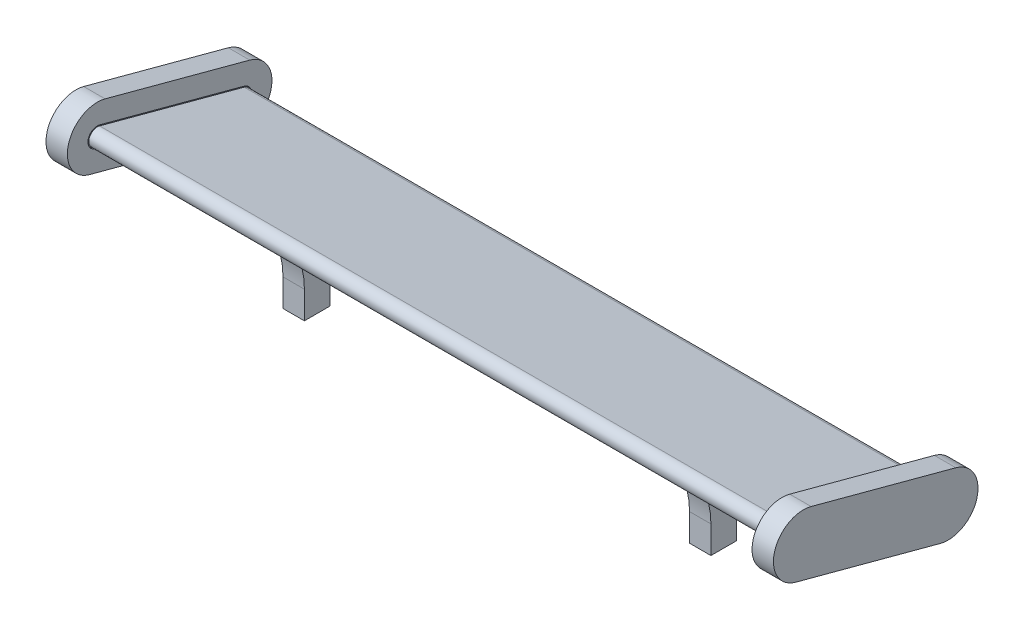
SolidWorks part; units mm, degrees
ref_plane "Front Plane" through (0, 0, 0) normal (0, 0, 1) x (1, 0, 0)
ref_plane "Top Plane" through (0, 0, 0) normal (0, 1, 0) x (1, 0, 0)
ref_plane "Right Plane" through (0, 0, 0) normal (1, 0, 0) x (0, 0, -1)
sketch "Sketch1" plane through (0, 0, 0) normal (1, 0, 0) x (0, 0, -1)
  line L0 (-16.9037, 4.5293) -> (16.9037, -4.5293) construction
  line L1 (-16.3867, 6.4589) -> (17.4207, -2.5997)
  line L2 (-17.4207, 2.5997) -> (16.3867, -6.4589)
  line L3 (0, 0) -> (31.3871, 0) construction
  arc A0 (-16.3867, 6.4589) -> (-17.4207, 2.5997) centre (-16.9037, 4.5293) ccw
  arc A1 (16.3867, -6.4589) -> (17.4207, -2.5997) centre (16.9037, -4.5293) ccw
  point P2 (0, 0)
  dimension "D1" = 15
  dimension "D2" = 35
  dimension "D3" = 3.9954
extrude "Boss-Extrude1" add sketch "Sketch1" along normal blind 80
sketch "Sketch2" plane through (80, 0, 0) normal (1, 0, 0) x (0, 0, -1)
  line L4 (-18.7148, -2.2299) -> (15.0926, -11.2886)
  line L5 (18.7148, 2.2299) -> (-15.0926, 11.2886)
  line L6 (-18.7148, -2.2299) -> (15.0926, -11.2886)
  line L7 (18.7148, 2.2299) -> (-15.0926, 11.2886)
  arc A4 (-15.0926, 11.2886) -> (-18.7148, -2.2299) centre (-16.9037, 4.5293) ccw
  arc A5 (15.0926, -11.2886) -> (18.7148, 2.2299) centre (16.9037, -4.5293) ccw
  arc A6 (-15.0926, 11.2886) -> (-18.7148, -2.2299) centre (-16.9037, 4.5293) ccw
  arc A7 (15.0926, -11.2886) -> (18.7148, 2.2299) centre (16.9037, -4.5293) ccw
  dimension "D1" = 5
extrude "Boss-Extrude2" add sketch "Sketch2" along normal blind 5 separate body
sketch "Sketch8" plane through (80, 0, 0) normal (-1, 0, 0) x (0, 0, 1)
  line L0 (17.4207, 2.5997) -> (-16.3867, -6.4589) construction
  line L1 (-17.4207, -2.5997) -> (16.3867, 6.4589) construction
  line L2 (17.4207, 2.5997) -> (-16.3867, -6.4589) construction
  line L3 (-17.4207, -2.5997) -> (16.3867, 6.4589) construction
  line L4 (-17.4725, -2.4065) -> (16.3349, 6.6521)
  line L5 (17.4725, 2.4065) -> (-16.3349, -6.6521)
  arc A0 (17.4207, 2.5997) -> (16.3867, 6.4589) centre (16.9037, 4.5293) ccw construction
  arc A1 (-17.4207, -2.5997) -> (-16.3867, -6.4589) centre (-16.9037, -4.5293) ccw construction
  arc A2 (17.4207, 2.5997) -> (16.3867, 6.4589) centre (16.9037, 4.5293) ccw construction
  arc A3 (-17.4207, -2.5997) -> (-16.3867, -6.4589) centre (-16.9037, -4.5293) ccw construction
  arc A4 (17.4725, 2.4065) -> (16.3349, 6.6521) centre (16.9037, 4.5293) ccw
  arc A5 (-17.4725, -2.4065) -> (-16.3349, -6.6521) centre (-16.9037, -4.5293) ccw
  dimension "D1" = 0.2
extrude "Cut-Extrude1" cut sketch "Sketch8" against normal blind 0.6 contours L4 A4 L5 A5
sketch "Sketch7" plane through (0, 0, 0) normal (-1, 0, 0) x (0, 0, 1)
  line L0 (0.517, -1.9296) -> (0.517, -21.9296) construction
  line L2 (-2.483, -17.1276) -> (-2.483, -21.9296)
  line L3 (3.517, -15.5199) -> (3.517, -21.9296)
  line L4 (3.517, -1.9296) -> (3.517, -21.9296) construction
  line L6 (-2.483, -1.9296) -> (-2.483, -21.9296) construction
  line L7 (-2.483, -21.9296) -> (3.517, -21.9296)
  line L8 (-6.7893, -5.9579) -> (6.1055, -2.5028) construction
  line L9 (16.3867, 6.4589) -> (-17.4207, -2.5997)
  line L10 (-16.3867, -6.4589) -> (17.4207, 2.5997)
  line L12 (-16.3867, -6.4589) -> (17.4207, 2.5997)
  line L13 (1.517, -15.5199) -> (1.517, -19.9296) construction
  line L14 (-0.483, -19.9296) -> (1.517, -19.9296) construction
  line L15 (-0.483, -17.1276) -> (-0.483, -19.9296) construction
  arc A0 (-16.3867, -6.4589) -> (-2.483, -17.1276) centre (-13.528, -17.1276) cw
  arc A1 (17.4207, 2.5997) -> (3.517, -15.5199) centre (22.2759, -15.5199) ccw
  arc A2 (17.4207, 2.5997) -> (16.3867, 6.4589) centre (16.9037, 4.5293) ccw
  arc A3 (-17.4207, -2.5997) -> (-16.3867, -6.4589) centre (-16.9037, -4.5293) ccw
  arc A6 (6.1055, -2.5028) -> (1.517, -15.5199) centre (22.2759, -15.5199) ccw construction
  arc A7 (-6.7893, -5.9579) -> (-0.483, -17.1276) centre (-13.528, -17.1276) cw construction
  point P2 (0, 0)
  point P3 (0, 0)
  dimension "D5" = 2
  dimension "D1" = 20
  dimension "D2" = 3
  dimension "D6" = 0.517
  dimension "D3" = 3
  dimension "D4" = 0
extrude "Boss-Extrude5" add sketch "Sketch7" along normal blind 5 from offset 50 offset against normal yes
mirror "Mirror3" about plane through (0, 4.5293, 16.9037) normal (1, 0, 0) of bodies 111
mirror "Mirror1" about plane through (0, 4.5293, 16.9037) normal (1, 0, 0) of "Boss-Extrude5", "Boss-Extrude1"
